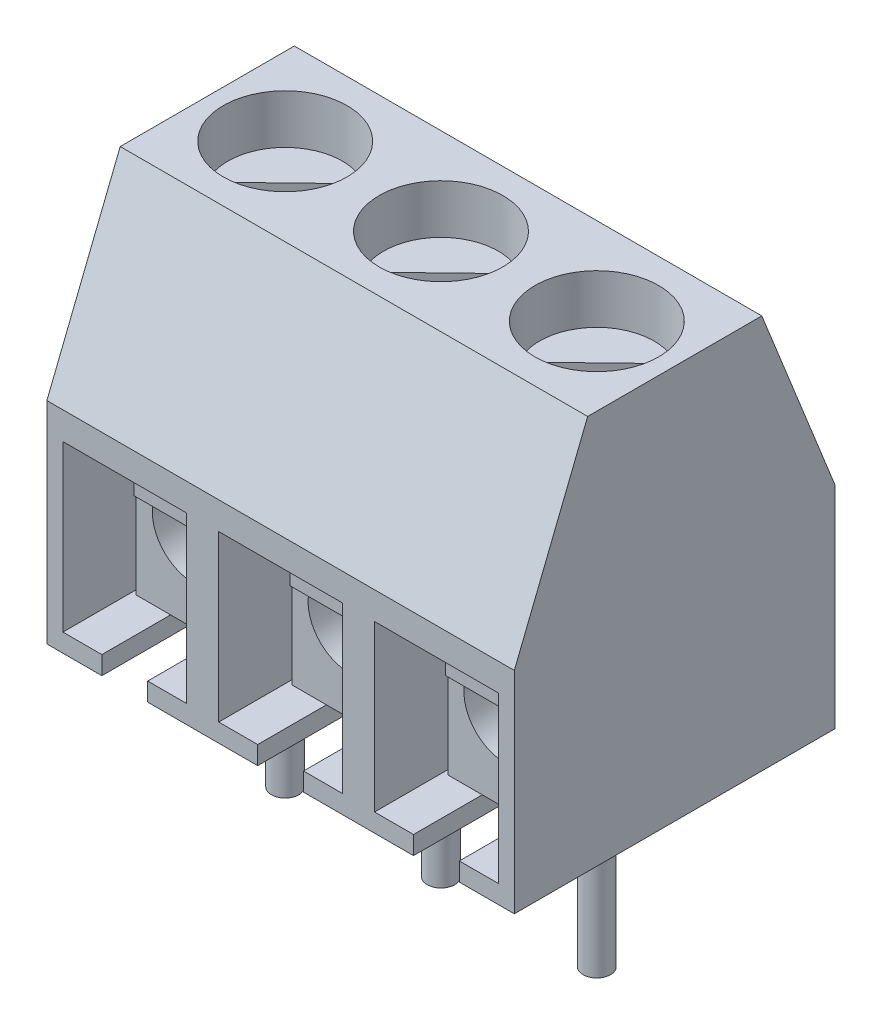
SolidWorks part; units mm, degrees
ref_plane "Plan de face" through (0, 0, 0) normal (0, 0, 1) x (1, 0, 0)
ref_plane "Plan de dessus" through (0, 0, 0) normal (0, 1, 0) x (1, 0, 0)
ref_plane "Plan de droite" through (0, 0, 0) normal (1, 0, 0) x (0, 0, -1)
sketch "Esquisse1" plane through (0, 0, 0) normal (1, 0, 0) x (0, 0, -1)
  line L0 (0, 0) -> (0, 4.6)
  line L1 (0, 4.6) -> (1.6, 8.6)
  line L2 (1.6, 8.6) -> (5.4, 8.6)
  line L3 (7, 4.6) -> (7, 0)
  line L4 (7, 0) -> (0, 0)
  line L5 (5.4, 8.6) -> (7, 4.6)
  line L6 (3.5, 0) -> (3.5, 8.6) construction
  dimension "D1" = 7
  dimension "D2" = 8.6
  dimension "D3" = 3.8
  dimension "D4" = 4
extrude "Boss.-Extru.1" add sketch "Esquisse1" along normal blind 3.4
sketch "Esquisse2" plane through (0, 0, 0) normal (0, 0, 1) x (1, 0, 0)
  line L0 (1.7, 0) -> (1.7, 0.4) construction
  line L1 (0.35, 0.4) -> (1.2, 0.4)
  line L2 (0.35, 0.4) -> (0.35, 4)
  line L3 (0.35, 4) -> (3.05, 4)
  line L4 (3.05, 0.4) -> (3.05, 4)
  line L5 (3.4, 0) -> (0, 0) construction
  line L6 (1.2, 0.4) -> (1.2, 0)
  line L7 (2.2, 0.4) -> (2.2, 0)
  line L8 (2.2, 0.4) -> (3.05, 0.4)
  line L9 (1.2, 0.4) -> (2.2, 0.4) construction
  line L10 (1.2, 0) -> (2.2, 0)
  dimension "D1" = 2.7
  dimension "D2" = 3.6
  dimension "D3" = 0.4
  dimension "D4" = 1
extrude "Enlèv. mat.-Extru.1" cut sketch "Esquisse2" against normal blind 6
sketch "Esquisse3" plane through (0, 8.6, 0) normal (0, 1, 0) x (1, 0, 0)
  line L0 (0, 5.4) -> (3.4, 1.6) construction
  line L1 (3.4, 5.4) -> (0, 1.6) construction
  circle A0 centre (1.7, 3.5) radius 1.35
  dimension "D1" = 2.7
extrude "Enlèv. mat.-Extru.2" cut sketch "Esquisse3" against normal up to next
sketch "Esquisse4" plane through (0, 8.6, 0) normal (0, 1, 0) x (1, 0, 0)
  circle A0 centre (1.7, 3.5) radius 1.25
  dimension "D1" = 2.5
extrude "Boss.-Extru.2" add sketch "Esquisse4" against normal blind 3.4 from offset 1 separate body offset against normal yes
sketch "Esquisse5" plane through (0, 7.6, 0) normal (0, 1, 0) x (1, 0, 0)
  line L0 (0.6187, 2.8729) -> (2.3645, 4.5587)
  line L1 (2.7813, 4.1271) -> (1.0355, 2.4413)
  line L2 (2.3645, 4.5587) -> (1.0355, 2.4413) construction
  line L3 (2.7813, 4.1271) -> (0.6187, 2.8729) construction
  line L4 (1.7, 3.5) -> (1.7, 5.2577) construction
  circle A0 centre (1.7, 3.5) radius 1.25 construction
  arc A1 (0.6187, 2.8729) -> (1.0355, 2.4413) centre (1.7, 3.5) ccw
  arc A2 (2.3645, 4.5587) -> (2.7813, 4.1271) centre (1.7, 3.5) cw
  dimension "D1" = 0.6
  dimension "D2" = 46
extrude "Enlèv. mat.-Extru.3" cut sketch "Esquisse5" against normal blind 0.4
sketch "Esquisse6" plane through (0, 0, 0) normal (0, 0, 1) x (1, 0, 0)
  line L0 (0.35, 0.4) -> (1.2, 0.4) construction
  line L1 (0.45, 0.4) -> (2.95, 0.4)
  line L2 (0.45, 0.4) -> (0.45, 3.9)
  line L3 (0.45, 3.9) -> (0.95, 3.9)
  line L4 (2.95, 0.4) -> (2.95, 3.9)
  line L5 (3.05, 4) -> (0.35, 4) construction
  line L7 (0.45, 3.9) -> (2.95, 0.4) construction
  line L8 (0.95, 3.9) -> (0.95, 3.65)
  line L9 (0.95, 3.65) -> (2.45, 3.65)
  line L10 (2.45, 3.65) -> (2.45, 3.9)
  line L11 (1.7, 2.15) -> (1.7, 4) construction
  line L12 (2.45, 3.9) -> (2.95, 3.9)
  circle A0 centre (1.7, 2.15) radius 0.9
  dimension "D3" = 1.8
  dimension "D1" = 3.5
  dimension "D2" = 2.5
  dimension "D4" = 1.5
  dimension "D5" = 0.25
extrude "Boss.-Extru.3" add sketch "Esquisse6" against normal up to surface (4.5 mm away) from offset 1.5 separate body up to face at (1.7, 1.2, -6) offset against normal yes
sketch "Esquisse7" plane through (0, 0.4, 0) normal (0, -1, 0) x (1, 0, 0)
  line L0 (1.7, -1.5) -> (1.7, -3.5) construction
  line L1 (0.45, -1.5) -> (2.95, -1.5) construction
  line L2 (1.2, 0) -> (0, 0) construction
  circle A0 centre (1.7, -3.5) radius 0.3
  dimension "D1" = 0.6
  dimension "D2" = 3.5
extrude "Boss.-Extru.4" add sketch "Esquisse7" along normal blind 4
ref_plane "Plan1" through (1.7, 0, 0) normal (1, 0, 0) x (0, 0, -1)
sketch "Esquisse8" plane through (1.7, 0, 0) normal (1, 0, 0) x (0, 0, -1)
  line L0 (2.15, 3.8) -> (1.5, 3.8)
  line L1 (1, 3.3) -> (1, 2.9)
  line L2 (1, 2.9) -> (2.4555, 1.6787)
  line L3 (2.15, 8.6) -> (2.15, 4) construction
  line L4 (6, 3.65) -> (1.5, 3.65) construction
  line L5 (1.5, 0.4) -> (1.5, 3.9) construction
  arc A0 (1.5, 3.8) -> (1, 3.3) centre (1.5, 3.3) ccw
  dimension "D2" = 0.5
  dimension "D1" = 0.15
  dimension "D3" = 0.4
  dimension "D4" = 1.9
  dimension "D5" = 130
extrude "Extru.-Mince1" add sketch "Esquisse8" along normal mid plane 1.4 separate body thin thin type mid plane wall 0.2
pattern_linear "Répétition linéaire2" count 3 spacing 3.4 along (1, 0, 0) of "Boss.-Extru.1", "Enlèv. mat.-Extru.2", "Enlèv. mat.-Extru.1"
pattern_linear "Répétition linéaire3" count 3 spacing 3.4 along (1, 0, 0) of bodies 107 108 105
